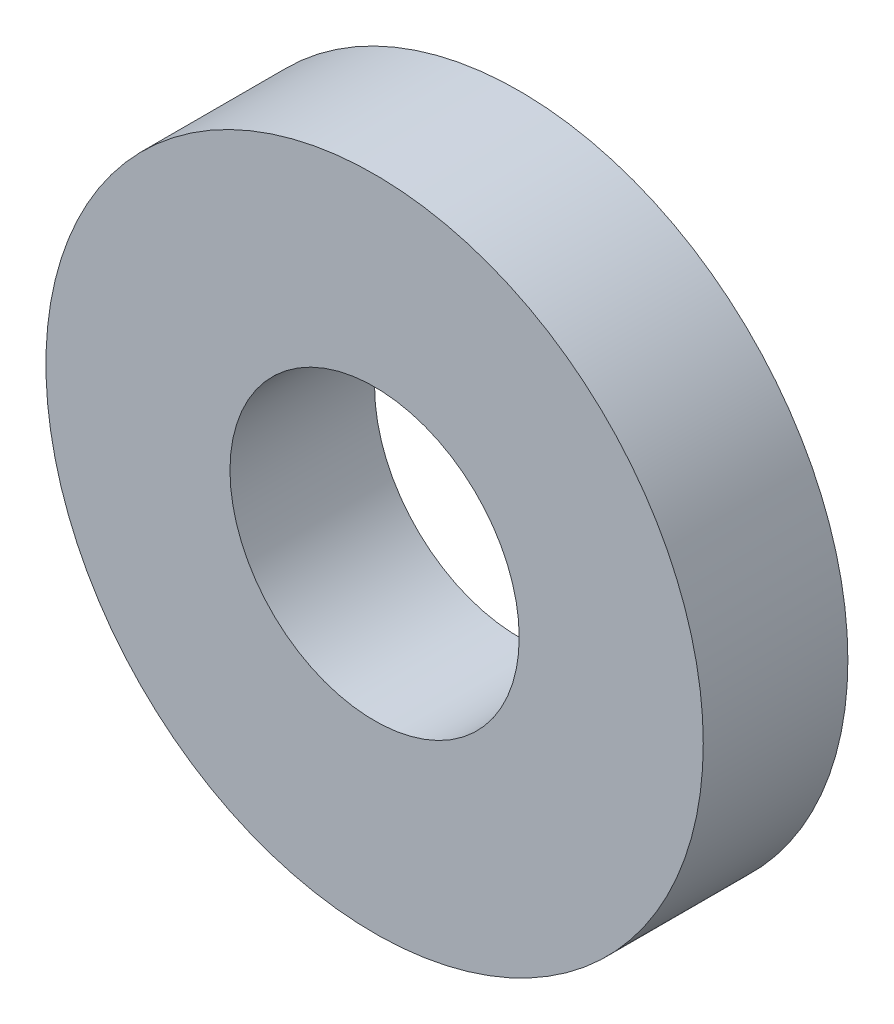
SolidWorks part; units mm, degrees
ref_plane "Front Plane" through (0, 0, 0) normal (0, 0, 1) x (1, 0, 0)
ref_plane "Top Plane" through (0, 0, 0) normal (0, 1, 0) x (1, 0, 0)
ref_plane "Right Plane" through (0, 0, 0) normal (1, 0, 0) x (0, 0, -1)
sketch "Sketch1" plane through (0, 0, 0) normal (0, 0, 1) x (1, 0, 0)
  circle A0 centre (0, 0) radius 2.5
  circle A1 centre (0, 0) radius 1.1
  dimension "OD" = 5
  dimension "ID1" = 2.2
extrude "Boss-Extrude1" add sketch "Sketch1" along normal blind 1.1
